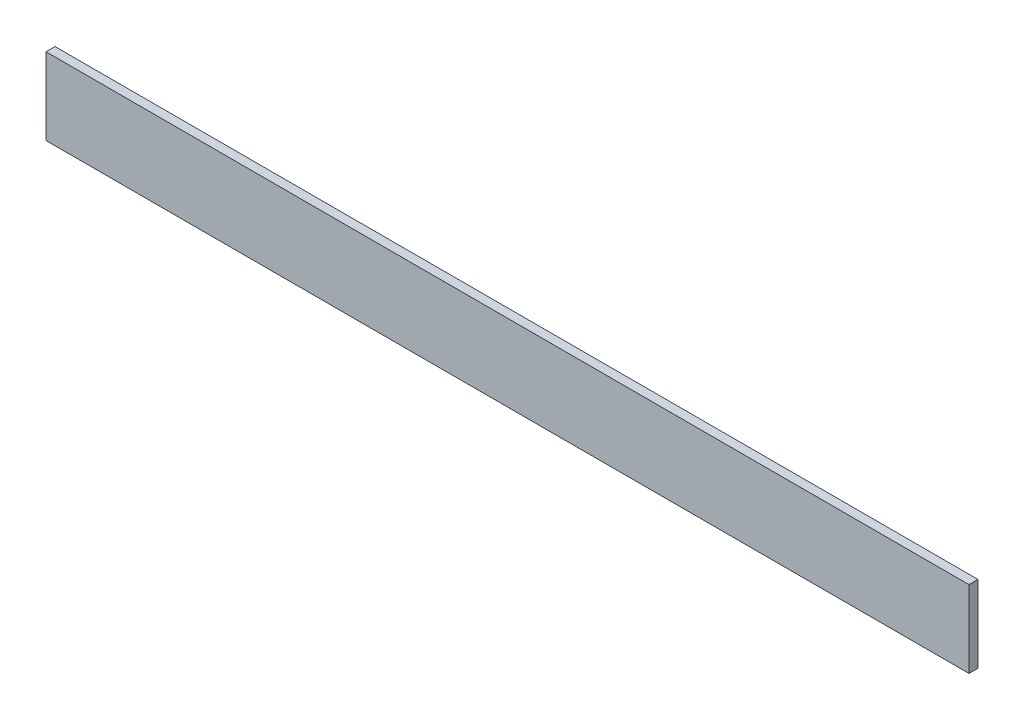
SolidWorks part; units mm, degrees
ref_plane "Front Plane" through (0, 0, 0) normal (0, 0, 1) x (1, 0, 0)
ref_plane "Top Plane" through (0, 0, 0) normal (0, 1, 0) x (1, 0, 0)
ref_plane "Right Plane" through (0, 0, 0) normal (1, 0, 0) x (0, 0, -1)
sketch "Sketch1" plane through (0, 0, 0) normal (0, 0, 1) x (1, 0, 0)
  line L1 (-609.6, -50.8) -> (609.6, -50.8)
  line L2 (-609.6, -50.8) -> (-609.6, 50.8)
  line L3 (-609.6, 50.8) -> (609.6, 50.8)
  line L4 (609.6, -50.8) -> (609.6, 50.8)
  line L5 (-609.6, -50.8) -> (609.6, 50.8) construction
  line L6 (-609.6, 50.8) -> (609.6, -50.8) construction
  point P0 (0, 0)
  dimension "D1" = 1219.2
  dimension "D2" = 101.6
extrude "Boss-Extrude1" add sketch "Sketch1" along normal blind 11.9062
